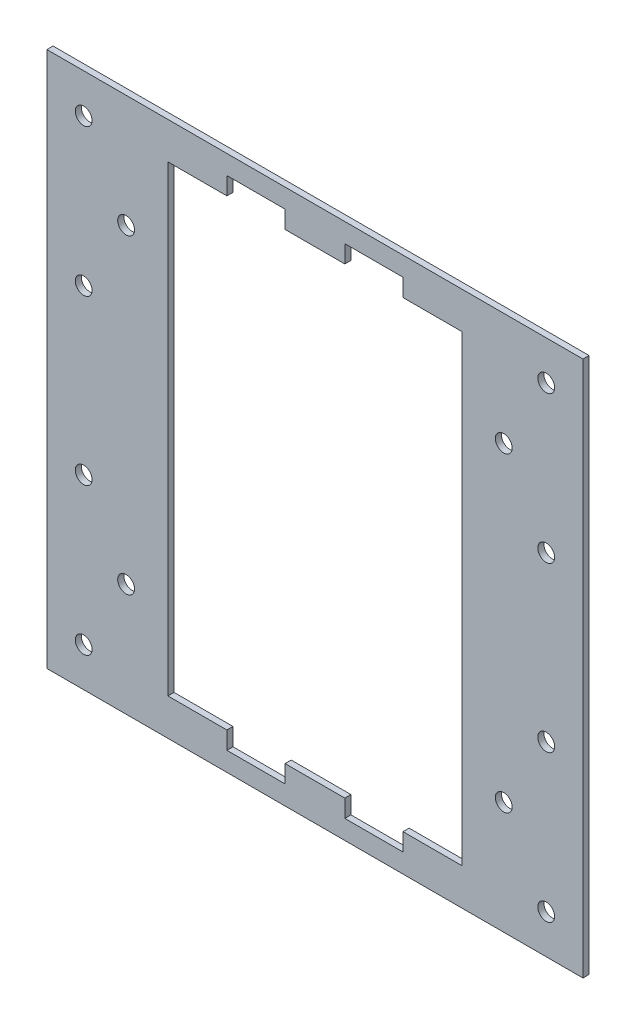
SolidWorks part; units mm, degrees
ref_plane "前视基准面" through (0, 0, 0) normal (0, 0, 1) x (1, 0, 0)
ref_plane "上视基准面" through (0, 0, 0) normal (0, 1, 0) x (1, 0, 0)
ref_plane "右视基准面" through (0, 0, 0) normal (1, 0, 0) x (0, 0, -1)
other "Configuration Table"
sketch "草图1" plane through (0, 0, 0) normal (0, 0, 1) x (1, 0, 0)
  line L0 (0, 0) -> (700, 0)
  line L1 (700, 0) -> (700, 700)
  line L2 (700, 700) -> (0, 700)
  line L3 (0, 700) -> (0, 0)
  dimension "width" = 700
  dimension "height" = 700
extrude "Connection_plate" add sketch "草图1" along normal blind 8
sketch "草图2" plane through (0, 0, 8) normal (0, 0, 1) x (1, 0, 0)
  line L0 (235, 25) -> (311, 25)
  line L1 (311, 25) -> (311, 325)
  line L2 (311, 325) -> (235, 325)
  line L3 (235, 325) -> (235, 25)
  dimension "x0" = 235
  dimension "x1" = 311
  dimension "y0" = 25
  dimension "y2" = 325
extrude "Access_window" cut sketch "草图2" against normal through all
sketch "草图3" plane through (0, 0, 8) normal (0, 0, 1) x (1, 0, 0)
  line L0 (235, 375) -> (311, 375)
  line L1 (311, 375) -> (311, 675)
  line L2 (311, 675) -> (235, 675)
  line L3 (235, 675) -> (235, 375)
  dimension "x0" = 235
  dimension "x1" = 311
  dimension "y0" = 375
  dimension "y2" = 675
extrude "切除-拉伸2" cut sketch "草图3" against normal through all
sketch "草图4" plane through (0, 0, 8) normal (0, 0, 1) x (1, 0, 0)
  line L0 (389, 25) -> (465, 25)
  line L1 (465, 25) -> (465, 325)
  line L2 (465, 325) -> (389, 325)
  line L3 (389, 325) -> (389, 25)
  dimension "x0" = 389
  dimension "x1" = 465
  dimension "y0" = 25
  dimension "y2" = 325
extrude "切除-拉伸3" cut sketch "草图4" against normal through all
sketch "草图5" plane through (0, 0, 8) normal (0, 0, 1) x (1, 0, 0)
  line L0 (389, 375) -> (465, 375)
  line L1 (465, 375) -> (465, 675)
  line L2 (465, 675) -> (389, 675)
  line L3 (389, 675) -> (389, 375)
  dimension "x0" = 389
  dimension "x1" = 465
  dimension "y0" = 375
  dimension "y2" = 675
extrude "切除-拉伸4" cut sketch "草图5" against normal through all
sketch "草图6" plane through (0, 0, 8) normal (0, 0, 1) x (1, 0, 0)
  circle A0 centre (48, 51) radius 11
  dimension "diameter" = 22
  dimension "x" = 48
  dimension "y" = 51
extrude "Shaft_clearance" cut sketch "草图6" against normal through all
sketch "草图7" plane through (0, 0, 8) normal (0, 0, 1) x (1, 0, 0)
  circle A0 centre (48, 243) radius 11
  dimension "diameter" = 22
  dimension "x" = 48
  dimension "y" = 243
extrude "切除-拉伸6" cut sketch "草图7" against normal through all
sketch "草图8" plane through (0, 0, 8) normal (0, 0, 1) x (1, 0, 0)
  circle A0 centre (48, 457) radius 11
  dimension "diameter" = 22
  dimension "x" = 48
  dimension "y" = 457
extrude "切除-拉伸7" cut sketch "草图8" against normal through all
sketch "草图9" plane through (0, 0, 8) normal (0, 0, 1) x (1, 0, 0)
  circle A0 centre (48, 649) radius 11
  dimension "diameter" = 22
  dimension "x" = 48
  dimension "y" = 649
extrude "切除-拉伸8" cut sketch "草图9" against normal through all
sketch "草图10" plane through (0, 0, 8) normal (0, 0, 1) x (1, 0, 0)
  circle A0 centre (103.43, 147) radius 11
  dimension "diameter" = 22
  dimension "x" = 103.43
  dimension "y" = 147
extrude "切除-拉伸9" cut sketch "草图10" against normal through all
sketch "草图11" plane through (0, 0, 8) normal (0, 0, 1) x (1, 0, 0)
  circle A0 centre (103.43, 553) radius 11
  dimension "diameter" = 22
  dimension "x" = 103.43
  dimension "y" = 553
extrude "切除-拉伸10" cut sketch "草图11" against normal through all
sketch "草图12" plane through (0, 0, 8) normal (0, 0, 1) x (1, 0, 0)
  circle A0 centre (652, 51) radius 11
  dimension "diameter" = 22
  dimension "x" = 652
  dimension "y" = 51
extrude "切除-拉伸11" cut sketch "草图12" against normal through all
sketch "草图13" plane through (0, 0, 8) normal (0, 0, 1) x (1, 0, 0)
  circle A0 centre (652, 243) radius 11
  dimension "diameter" = 22
  dimension "x" = 652
  dimension "y" = 243
extrude "切除-拉伸12" cut sketch "草图13" against normal through all
sketch "草图14" plane through (0, 0, 8) normal (0, 0, 1) x (1, 0, 0)
  circle A0 centre (652, 457) radius 11
  dimension "diameter" = 22
  dimension "x" = 652
  dimension "y" = 457
extrude "切除-拉伸13" cut sketch "草图14" against normal through all
sketch "草图15" plane through (0, 0, 8) normal (0, 0, 1) x (1, 0, 0)
  circle A0 centre (652, 649) radius 11
  dimension "diameter" = 22
  dimension "x" = 652
  dimension "y" = 649
extrude "切除-拉伸14" cut sketch "草图15" against normal through all
sketch "草图16" plane through (0, 0, 8) normal (0, 0, 1) x (1, 0, 0)
  circle A0 centre (596.57, 147) radius 11
  dimension "diameter" = 22
  dimension "x" = 596.57
  dimension "y" = 147
extrude "切除-拉伸15" cut sketch "草图16" against normal through all
sketch "草图17" plane through (0, 0, 8) normal (0, 0, 1) x (1, 0, 0)
  circle A0 centre (596.57, 553) radius 11
  dimension "diameter" = 22
  dimension "x" = 596.57
  dimension "y" = 553
extrude "切除-拉伸16" cut sketch "草图17" against normal through all
sketch "草图18" plane through (0, 0, 8) normal (0, 0, 1) x (1, 0, 0)
  line L0 (158, 48) -> (542, 48)
  line L1 (542, 48) -> (542, 652)
  line L2 (542, 652) -> (158, 652)
  line L3 (158, 652) -> (158, 48)
  dimension "x0" = 158
  dimension "x1" = 542
  dimension "y0" = 48
  dimension "y2" = 652
extrude "Float_installation_window" cut sketch "草图18" against normal through all
